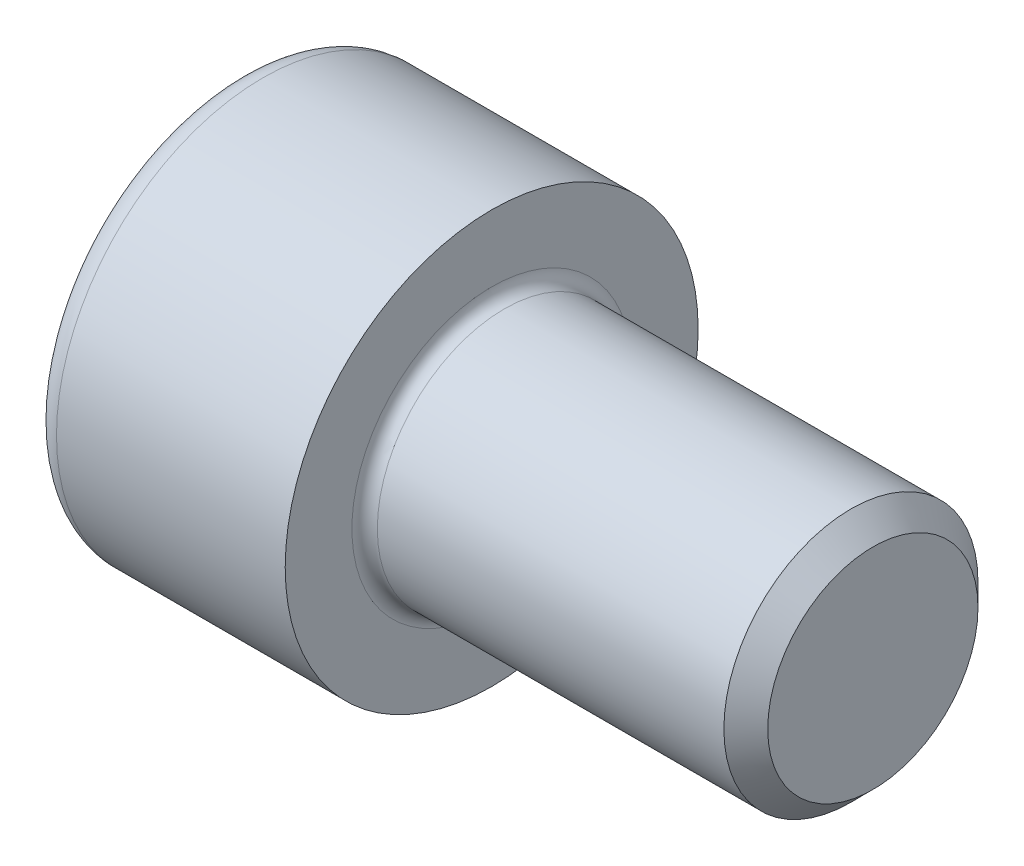
SolidWorks part; units mm, degrees
revolve "Base-Revolve" add sketch "BodySke"
sketch "BodySke" plane through (0, 0, 0) normal (0, 0, 1) x (1, 0, 0)
  line L0 (0, 0) -> (0, 6.5)
  line L1 (0, 6.5) -> (8, 6.5)
  line L2 (8, 6.5) -> (8, 4)
  line L3 (8, 4) -> (19.3095, 4)
  line L4 (20, 3.3095) -> (20, 0)
  line L5 (20, 0) -> (0, 0)
  line L6 (-31.75, 0) -> (127, 0) construction
  line L8 (20, 3.3095) -> (19.3095, 4)
  line L10 (20, -3.3095) -> (19.3095, -4) construction
  line L11 (9.25, 9.525) -> (9.25, 3.175) construction
  line L12 (8, 9.525) -> (8, 3.175) construction
  line L13 (-40, 9.525) -> (-40, 3.175) construction
  dimension "Head_ht" = 8
  dimension "Length" = 12
  dimension "Body_ch_ang" = 45
  dimension "Diameter" = 8
  dimension "Minor_dia" = 6.619
  dimension "Advance" = 1.25
  dimension "Thread_nom" = 12
  dimension "Thread_length" = 60
  dimension "Head_dia" = 13
cosmetic thread "ThreadCosmetic" [suppressed]
fillet "Fillet1" radius 0.4 1 edges at (8, 0, 4)
fillet "Fillet2" radius 0.8 1 edges at (0, 0, 6.5)
ref_plane "Plane1" through (0, 0, 0) normal (0, 0, 1) x (1, 0, 0)
ref_plane "Plane2" through (0, 0, 0) normal (0, 1, 0) x (1, 0, 0)
ref_plane "Plane3" through (0, 0, 0) normal (1, 0, 0) x (0, 0, -1)
other "Configuration Table"
sketch "Sketch2" plane through (0, 0, 0) normal (0, 0, 1) x (1, 0, 0)
  line L0 (0, 3.01) -> (4, 3.01)
  line L1 (4, 3.01) -> (5.7378, 0)
  line L2 (-31.75, 0) -> (127, 0) construction
  line L3 (5.7378, 0) -> (0, 0)
  line L4 (0, 0) -> (0, 3.01)
  line L6 (0, 0) -> (47.625, 0) construction
  dimension "D1" = 3.01
  dimension "D2" = 60
  dimension "Depth" = 4
revolve "Hex-PreBroach" cut sketch "Sketch2" angle 360 about L6
sketch "Sketch3" plane through (0, 0, 0) normal (-1, 0, 0) x (0, 0.5, 0.866)
  line L0 (1.7378, 3.01) -> (-1.7378, 3.01)
  line L1 (-1.7378, 3.01) -> (-3.4756, 0)
  line L2 (1.7378, 3.01) -> (3.4756, 0)
  line L3 (1.7378, -3.01) -> (3.4756, 0)
  line L4 (1.7378, -3.01) -> (-1.7378, -3.01)
  line L5 (-1.7378, -3.01) -> (-3.4756, 0)
  dimension "D1" = 3.01
  dimension "D2" = 3.01
  dimension "Hex_size" = 6.02
extrude "Hex" cut sketch "Sketch3" against normal blind 4
sketch "ThdSchSke" plane through (0, 0, 0) normal (0, 0, 1) x (1, 0, 0)
  line L0 (11.75, -3.3095) -> (11.2665, -4)
  line L1 (11.75, -3.3095) -> (12.2335, -4)
  line L2 (12.2335, -4) -> (12.2335, -5)
  line L3 (-3.175, 0) -> (5.1513, 0) construction
  line L4 (0, 5.7) -> (0, -5.7) construction
  line L5 (12.2335, -5) -> (11.2665, -5)
  line L6 (11.2665, -5) -> (11.2665, -4)
  dimension "Thread_minor" = 6.619
  dimension "Diameter" = 8
  dimension "Start" = 11.75
revolve "ThreadSchematic" [suppressed] cut sketch "ThdSchSke" angle 360 about L3
pattern_linear "ThdSchPat" [suppressed]
equation "\"D2@Sketch3\" = \"Hex_size@Sketch3\" / 2"
equation "\"D1@Sketch3\" = \"Hex_size@Sketch3\" / 2"
equation "\"D1@Sketch2\" = \"Hex_size@Sketch3\" / 2"
equation "\"Thread_minor@ThreadCosmetic\"  =  \"Minor_dia@BodySke\""
equation "\"Depth@Sketch2\" =  \"Key_eng@Hex\""
equation "\"Thread_length@ThreadCosmetic\" = ((sgn( (\"Length@BodySke\" - \"Advance@BodySke\" * 3.0) - \"Thread_nom@BodySke\" )-1)*( (\"Length@BodySke\" - \"Advance@BodySke\" * 3.0) - \"Thread_nom@BodySke\" ))/-2+ \"Thread_nom@BodySke\""
equation "\"Thread_minor@ThdSchSke\" = \"Minor_dia@BodySke\""
equation "\"Diameter@ThdSchSke\" = \"Diameter@BodySke\""
equation "\"Overcut@ThdSchSke\" = \"Diameter@BodySke\" * 1.25"
equation "\"Start@ThdSchSke\" = \"Head_ht@BodySke\" + \"Length@BodySke\" - \"Thread_length@ThreadCosmetic\"  '---Non-countersunk---"
equation "\"Num_threads@ThdSchPat\" = int( \"Thread_length@ThreadCosmetic\" / \"Advance@BodySke\" + 0.999 )  + 1"
equation "\"Advance@ThdSchPat\" = \"Thread_length@ThreadCosmetic\" /  (\"Num_threads@ThdSchPat\" - 1) 'relax it"
equation "\"Num_threads@ThdSchPat\" = \"Num_threads@ThdSchPat\" - sgn( \"Num_threads@ThdSchPat\" - 1) '---chamfered tips only---"
